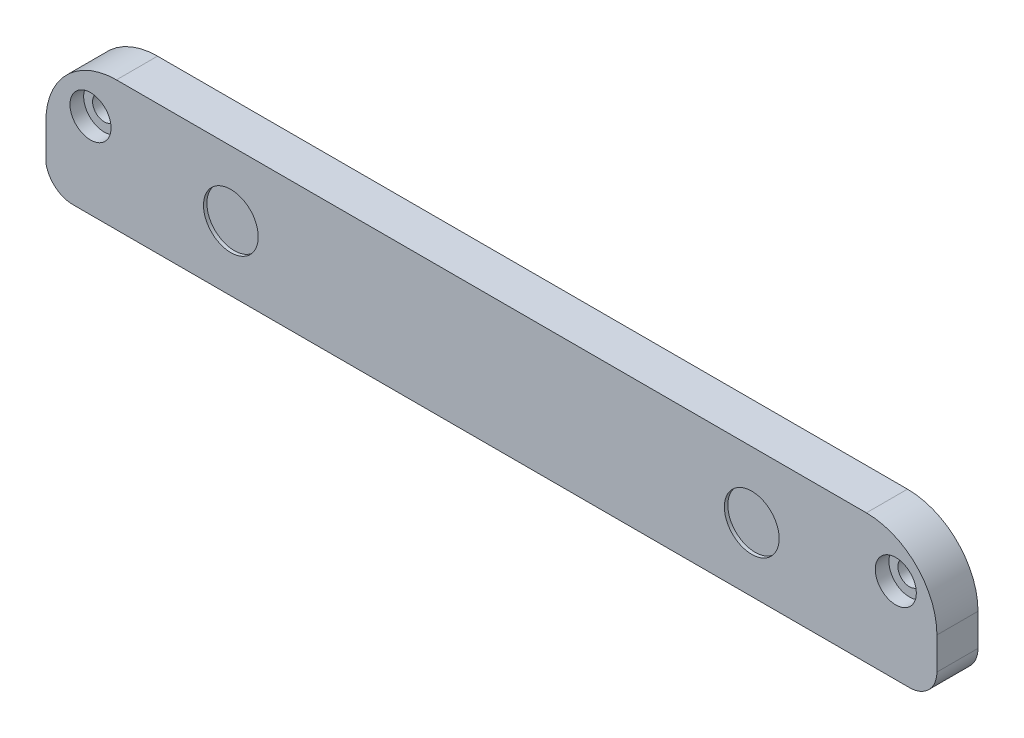
SolidWorks part; units mm, degrees
ref_plane "Ebene vorne" through (0, 0, 0) normal (0, 0, 1) x (1, 0, 0)
ref_plane "Ebene oben" through (0, 0, 0) normal (0, 1, 0) x (1, 0, 0)
ref_plane "Ebene rechts" through (0, 0, 0) normal (1, 0, 0) x (0, 0, -1)
sketch "Skizze1" plane through (0, 0, 0) normal (0, 0, 1) x (1, 0, 0)
  line L0 (-49.2275, -151.2967) -> (-49.2275, -51.8905) construction
  line L1 (-179.3474, -52.3842) -> (-179.3474, -150.8036) construction
  line L2 (-49.2275, -51.8905) -> (-49.2275, -56.5812)
  line L8 (-175.4204, -60.5561) -> (-53.2274, -60.5561)
  line L12 (-179.3474, -57.3168) -> (-179.3474, -52.3842)
  line L14 (-59.5275, -41.5905) -> (-169.0581, -41.5905) construction
  line L15 (-59.5275, -41.5905) -> (-169.0581, -41.5905)
  arc A0 (-49.2275, -51.8905) -> (-59.5275, -41.5905) centre (-59.5275, -51.8905) ccw construction
  arc A1 (-49.2275, -51.8905) -> (-59.5275, -41.5905) centre (-59.5275, -51.8905) ccw
  arc A19 (-169.0581, -41.5905) -> (-179.3474, -52.3842) centre (-169.0581, -51.8916) ccw construction
  arc A20 (-53.2274, -60.5561) -> (-49.2275, -56.5812) centre (-53.2274, -56.5561) ccw
  arc A21 (-175.4204, -60.5561) -> (-179.3474, -57.3168) centre (-175.4204, -56.5561) cw
  circle A22 centre (-55.2338, -48.0905) radius 1.7 construction
  circle A23 centre (-172.8474, -48.0905) radius 1.7 construction
  circle A24 centre (-55.2338, -48.0905) radius 1.7
  circle A25 centre (-172.8474, -48.0905) radius 1.7
  arc A26 (-169.0581, -41.5905) -> (-179.3474, -52.3842) centre (-169.0581, -51.8916) ccw
  dimension "D1" = 4
extrude "Aufsatz-Linear austragen1" add sketch "Skizze1" along normal blind 6
sketch "Skizze2" plane through (0, 0, 6) normal (0, 0, 1) x (1, 0, 0)
  line L0 (-59.5275, -41.5905) -> (-169.0581, -41.5905) construction
  line L1 (-179.3474, -57.3168) -> (-179.3474, -52.3842) construction
  line L2 (-114.2928, -41.5905) -> (-114.3239, -60.5561) construction
  line L3 (-175.4204, -60.5561) -> (-53.2274, -60.5561) construction
  circle A0 centre (-152.3474, -51.0905) radius 4
  circle A2 centre (-76.2696, -51.2154) radius 4
  dimension "D1" = 8
  dimension "D2" = 9.5
  dimension "D3" = 27
extrude "Schnitt-Linear austragen1" cut sketch "Skizze2" against normal blind 0.5
sketch "Skizze3" plane through (0, 0, 6) normal (0, 0, 1) x (1, 0, 0)
  circle A0 centre (-172.8474, -48.0905) radius 3
  circle A1 centre (-55.2338, -48.0905) radius 3
  dimension "D1" = 6
extrude "Schnitt-Linear austragen2" cut sketch "Skizze3" against normal blind 2
